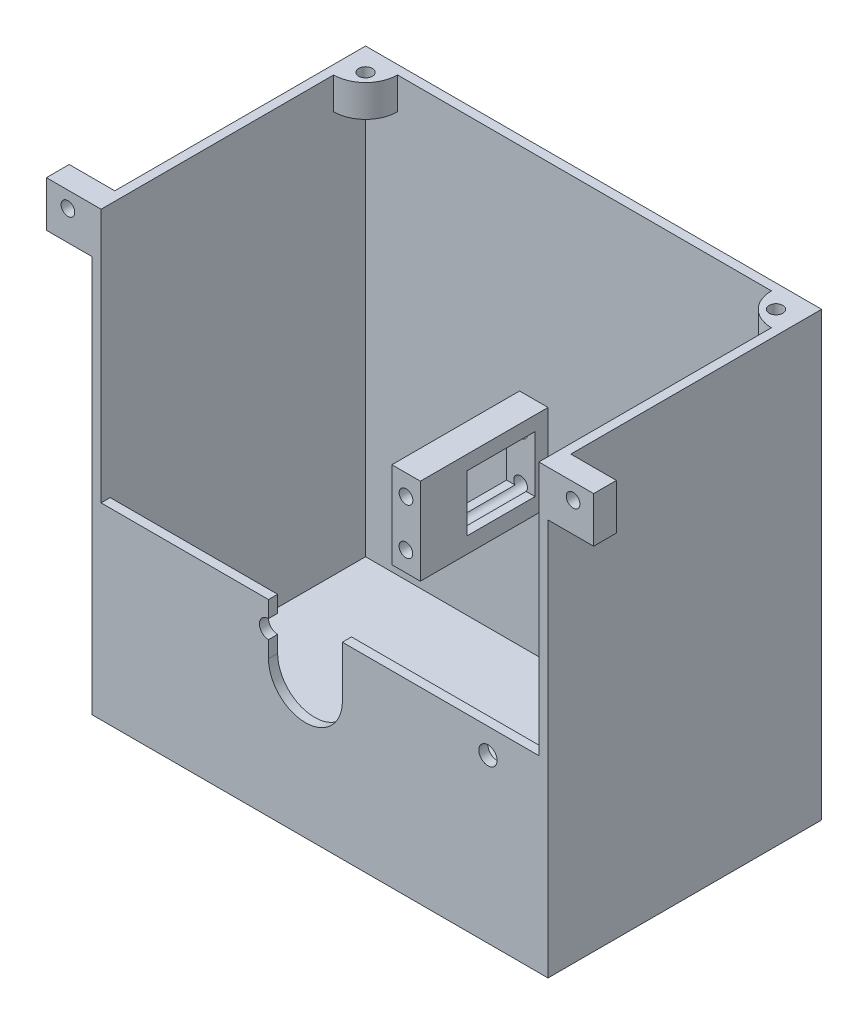
SolidWorks part; units mm, degrees
ref_plane "Front Plane" through (0, 0, 0) normal (0, 0, 1) x (1, 0, 0)
ref_plane "Top Plane" through (0, 0, 0) normal (0, 1, 0) x (1, 0, 0)
ref_plane "Right Plane" through (0, 0, 0) normal (1, 0, 0) x (0, 0, -1)
sketch "Sketch1" plane through (0, 0, 0) normal (0, 0, 1) x (1, 0, 0)
  line L0 (-47.6718, 33.255) -> (-47.6718, 35.255)
  line L1 (-49.6674, 35.255) -> (-47.6718, 35.255)
  line L2 (-49.6674, 35.255) -> (-49.6674, -64.745)
  line L3 (-49.6674, -64.745) -> (50.3326, -64.745)
  line L4 (50.3326, 35.255) -> (50.3326, -64.745)
  line L6 (-47.6718, 33.255) -> (-47.6718, -62.745)
  line L7 (-47.6718, -62.745) -> (48.3326, -62.745)
  line L8 (48.3326, 33.255) -> (48.3326, -62.745)
  line L9 (48.3326, 33.255) -> (48.3326, 35.255)
  line L10 (48.3326, 35.255) -> (50.3326, 35.255)
  dimension "D1" = 100
  dimension "D2" = 100
  dimension "D3" = 1.9956
  dimension "D4" = 2
  dimension "D6" = 2
extrude "Boss-Extrude1" add sketch "Sketch1" along normal blind 70
sketch "Sketch2" plane through (0, 0, 0) normal (0, 0, -1) x (-1, 0, 0)
  line L1 (-50.3326, 35.255) -> (49.6674, 35.255)
  line L2 (-50.3326, 35.255) -> (-50.3326, -64.745)
  line L3 (-50.3326, -64.745) -> (49.6674, -64.745)
  line L4 (49.6674, 35.255) -> (49.6674, -64.745)
extrude "Boss-Extrude2" add sketch "Sketch2" along normal blind 2 contours L1 L4 L3 L2
sketch "Sketch3" plane through (0, 0, 0) normal (0, 0, 1) x (1, 0, 0)
  line L0 (33.9342, -14.383) -> (33.9342, -33.383)
  line L1 (-7.6527, -14.383) -> (-13.9025, -14.383)
  line L3 (-7.6527, -33.383) -> (-13.9025, -33.383)
  line L4 (-13.9025, -14.383) -> (-13.9025, -33.383)
  line L5 (33.9342, -14.383) -> (40.1899, -14.383)
  line L7 (33.9342, -33.383) -> (40.1899, -33.383)
  line L8 (40.1899, -14.383) -> (40.1899, -33.383)
  line L9 (-7.6527, -14.383) -> (-7.6527, -33.383)
  circle A0 centre (37.1695, -19.0297) radius 1.5
  circle A1 centre (37.1899, -28.9161) radius 1.5
  circle A2 centre (-10.8058, -18.883) radius 1.5
  circle A3 centre (-10.8305, -29.0297) radius 1.5
extrude "Boss-Extrude4" add sketch "Sketch3" along normal blind 28
sketch "Sketch4" plane through (33.9342, 0, 0) normal (-1, 0, 0) x (0, 0, 1)
  line L0 (28, -33.383) -> (0, -33.383) construction
  line L1 (17.7261, -17.5315) -> (2.8469, -17.5315)
  line L2 (17.7261, -17.5315) -> (17.7261, -29.883)
  line L3 (17.7261, -29.883) -> (2.8469, -29.883)
  line L4 (2.8469, -17.5315) -> (2.8469, -29.883)
  dimension "D1" = 3.5
extrude "Cut-Extrude2" cut sketch "Sketch4" against normal blind 10 and the other way blind 49
sketch "Sketch5" plane through (0, 0, 70) normal (0, 0, 1) x (1, 0, 0)
  line L0 (-47.6718, -62.745) -> (-47.6718, 35.255) construction
  line L1 (48.3326, -62.745) -> (-47.6718, -62.745)
  line L2 (48.3326, -62.745) -> (48.3326, -19.0519)
  line L3 (48.3326, -19.0519) -> (-47.6718, -19.0519)
  line L4 (-47.6718, -62.745) -> (-47.6718, -19.0519)
extrude "Boss-Extrude5" add sketch "Sketch5" against normal blind 2
sketch "Sketch8" plane through (0, 35.255, 0) normal (0, 1, 0) x (1, 0, 0)
  line L1 (-47.6718, 0) -> (-40.6718, 0)
  line L2 (48.3326, 0) -> (48.3326, -7)
  line L5 (-47.6718, -7) -> (-47.6718, 0)
  line L6 (41.3326, 0) -> (48.3326, 0)
  arc A0 (-47.6718, -7) -> (-40.6718, 0) centre (-47.6718, 0) ccw
  arc A1 (41.3326, 0) -> (48.3326, -7) centre (48.3326, 0) ccw
  circle A5 centre (45.3326, -3) radius 1.5
  circle A6 centre (-44.6718, -3) radius 1.5
  dimension "D1" = 3
  dimension "D2" = 3
  dimension "D7" = 3
  dimension "D8" = 3
ref_plane "Plane1" through (0, 0, -2) normal (0, 0, -1) x (-1, 0, 0)
ref_plane "Plane2" through (0, 0, 58) normal (0, 0, -1) x (-1, 0, 0)
sketch "Sketch9" plane through (0, 0, 58) normal (0, 0, -1) x (-1, 0, 0)
  line L1 (-50.3326, 35.255) -> (49.6674, 35.255)
  line L2 (-50.3326, 35.255) -> (-50.3326, -64.745)
  line L3 (-50.3326, -64.745) -> (49.6674, -64.745)
  line L4 (49.6674, 35.255) -> (49.6674, -64.745)
extrude "Cut-Extrude3" cut sketch "Sketch9" against normal blind 42 contours L2 L3 L4 L1
sketch "Sketch10" plane through (0, 0, 58) normal (0, 0, 1) x (1, 0, 0)
  line L0 (50.3326, 35.255) -> (50.3326, -64.745) construction
  line L1 (-49.6674, -64.745) -> (50.3326, -64.745)
  line L2 (-49.6674, -64.745) -> (-49.6674, -23.5151)
  line L3 (-49.6674, -23.5151) -> (-15.7694, -23.5151)
  line L4 (50.3326, -64.745) -> (50.3326, -23.5151)
  line L5 (-10.9579, -34.745) -> (-10.9579, -23.5151)
  line L8 (16.0922, -23.5151) -> (50.3326, -23.5151)
  line L9 (-10.9579, -23.5151) -> (-15.7694, -23.5151)
  line L10 (16.0922, -23.5151) -> (5.2421, -23.5151)
  line L11 (5.2421, -23.5151) -> (5.2421, -34.745)
  arc A1 (-10.9579, -34.745) -> (5.2421, -34.745) centre (-2.8579, -34.745) ccw
extrude "Boss-Extrude6" add sketch "Sketch10" against normal blind 2
extrude "Boss-Extrude7" add sketch "Sketch8" against normal blind 10
ref_plane "Plane3" through (0, 0, 58) normal (0, 0, 1) x (1, 0, 0)
sketch "Sketch11" plane through (0, 0, 58) normal (0, 0, 1) x (1, 0, 0)
  line L0 (-47.2315, 22.255) -> (-59.6674, 22.255) construction
  line L1 (-59.6674, 32.255) -> (-49.6674, 32.255)
  line L2 (-59.6674, 32.255) -> (-59.6674, 22.255)
  line L3 (-59.6674, 22.255) -> (-49.6674, 22.255)
  line L4 (-49.6674, 32.255) -> (-49.6674, 22.255)
  line L5 (-49.6674, 35.255) -> (-49.6674, -64.745) construction
  line L6 (50.3326, 35.255) -> (50.3326, -64.745) construction
  line L7 (60.3326, 32.255) -> (50.3326, 32.255)
  line L8 (60.3326, 32.255) -> (60.3326, 22.255)
  line L9 (60.3326, 22.255) -> (50.3326, 22.255)
  line L10 (50.3326, 32.255) -> (50.3326, 22.255)
  line L11 (60.3326, 22.255) -> (48.3326, 22.255) construction
  circle A0 centre (-54.9494, 28.755) radius 1.5
  circle A1 centre (55.8326, 28.755) radius 1.5
extrude "Boss-Extrude8" add sketch "Sketch11" against normal blind 5
sketch "Sketch13" plane through (0, 0, 58) normal (0, 0, 1) x (1, 0, 0)
  line L0 (-10.9579, -34.745) -> (-10.9579, -23.5151) construction
  circle A0 centre (-10.9579, -29.1301) radius 2
  circle A1 centre (37.1695, -29.0297) radius 2
extrude "Cut-Extrude4" cut sketch "Sketch13" against normal blind 10
sketch "Sketch15" plane through (0, 35.255, 0) normal (0, 1, 0) x (1, 0, 0)
  line L8 (-47.6718, -58) -> (-47.6718, -7)
  line L9 (-40.6718, 0) -> (41.3326, 0)
  line L10 (48.3326, -7) -> (48.3326, -58)
  line L11 (48.3326, -58) -> (50.3326, -58)
  line L12 (50.3326, -58) -> (50.3326, 2)
  line L13 (50.3326, 2) -> (-49.6674, 2)
  line L14 (-49.6674, 2) -> (-49.6674, -58)
  line L15 (-49.6674, -58) -> (-47.6718, -58)
  line L16 (-47.6718, -58) -> (-47.6718, -7)
  line L17 (-40.6718, 0) -> (41.3326, 0)
  line L18 (48.3326, -7) -> (48.3326, -58)
  line L19 (48.3326, -58) -> (50.3326, -58)
  line L20 (50.3326, -58) -> (50.3326, 2)
  line L21 (50.3326, 2) -> (-49.6674, 2)
  line L22 (-49.6674, 2) -> (-49.6674, -58)
  line L23 (-49.6674, -58) -> (-47.6718, -58)
  arc A2 (-47.6718, -7) -> (-40.6718, 0) centre (-47.6718, 0) ccw
  arc A3 (41.3326, 0) -> (48.3326, -7) centre (48.3326, 0) ccw
  arc A4 (-47.6718, -7) -> (-40.6718, 0) centre (-47.6718, 0) ccw
  arc A5 (41.3326, 0) -> (48.3326, -7) centre (48.3326, 0) ccw
  dimension "D1" = 0
extrude "Cut-Extrude5" cut sketch "Sketch15" against normal blind 3
sketch "Sketch16" plane through (0, -62.745, 0) normal (0, 1, 0) x (1, 0, 0)
  circle A0 centre (44.0168, -11.9057) radius 4.0028
  point P2 (0, 0)
  point P3 (44.0168, -11.9057)
extrude "Cut-Extrude7" cut sketch "Sketch16" against normal blind 3
